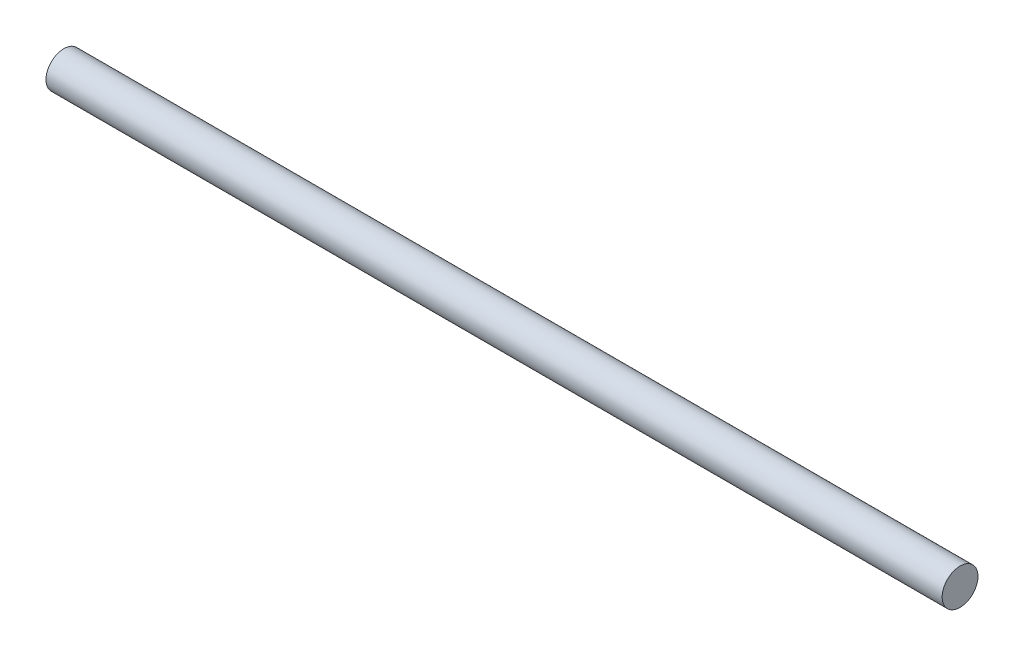
SolidWorks part; units mm, degrees
ref_plane "Front Plane" through (0, 0, 0) normal (0, 0, 1) x (1, 0, 0)
ref_plane "Top Plane" through (0, 0, 0) normal (0, 1, 0) x (1, 0, 0)
ref_plane "Right Plane" through (0, 0, 0) normal (1, 0, 0) x (0, 0, -1)
sketch "Sketch1" plane through (0, 0, 0) normal (1, 0, 0) x (0, 0, -1)
  circle A0 centre (0, 0) radius 4
extrude "Boss-Extrude1" add sketch "Sketch1" along normal blind 200
